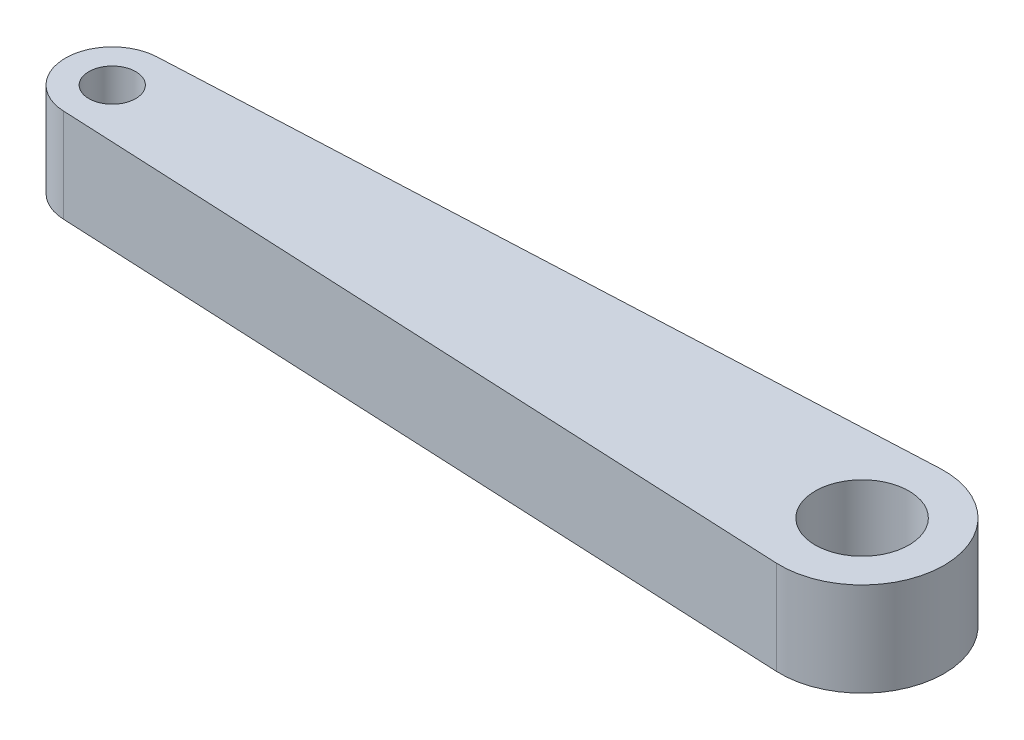
SolidWorks part; units mm, degrees
ref_plane "前视基准面" through (0, 0, 0) normal (0, 0, 1) x (1, 0, 0)
ref_plane "上视基准面" through (0, 0, 0) normal (0, 1, 0) x (1, 0, 0)
ref_plane "右视基准面" through (0, 0, 0) normal (1, 0, 0) x (0, 0, -1)
other "Configuration Table"
sketch "草图1" plane through (0, 0, 0) normal (0, 1, 0) x (1, 0, 0)
  line L0 (0, 0) -> (32, 0) construction
  line L1 (-0.0938, 1.9978) -> (31.8359, 3.4962)
  line L2 (-0.0938, -1.9978) -> (31.8359, -3.4962)
  arc A0 (-0.0938, 1.9978) -> (-0.0938, -1.9978) centre (0, 0) ccw
  circle A1 centre (0, 0) radius 1
  circle A2 centre (32, 0) radius 2
  arc A3 (31.8359, -3.4962) -> (31.8359, 3.4962) centre (32, 0) ccw
  dimension "D1" = 4
  dimension "D2" = 2
  dimension "D4" = 4
  dimension "D5" = 7
  dimension "D3" = 32
extrude "凸台-拉伸1" add sketch "草图1" along normal blind 4
